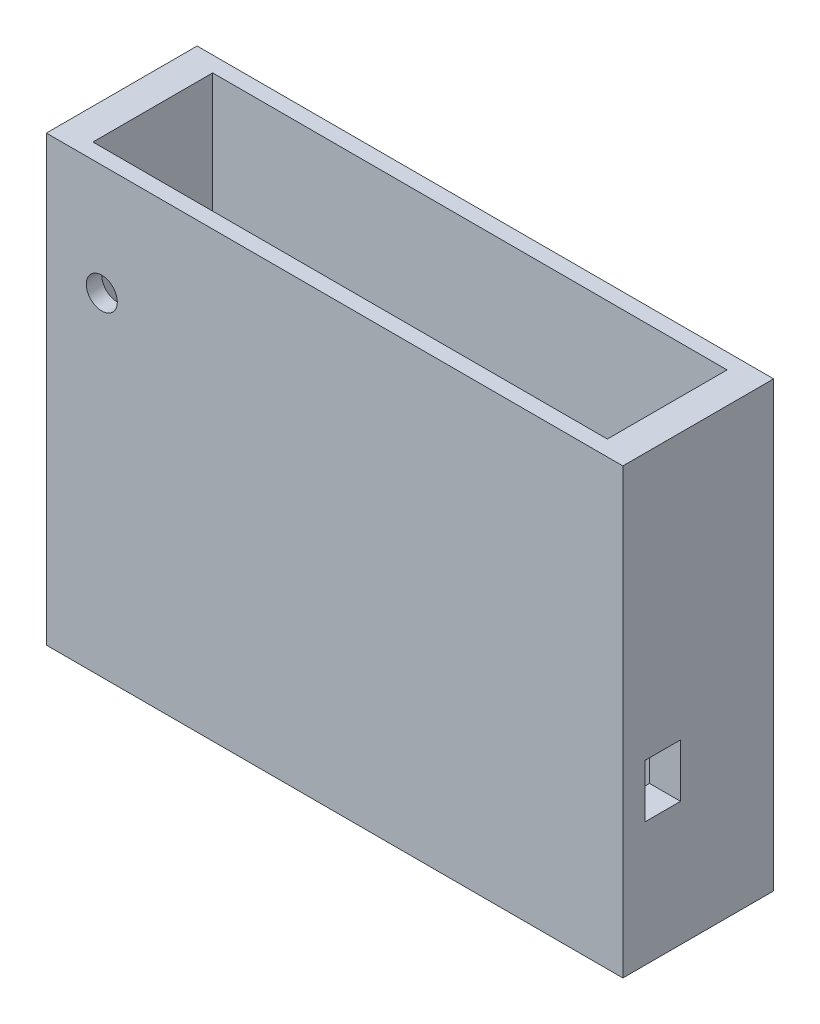
SolidWorks part; units mm, degrees
ref_plane "Plan de face" through (0, 0, 0) normal (0, 0, 1) x (1, 0, 0)
ref_plane "Plan de dessus" through (0, 0, 0) normal (0, 1, 0) x (1, 0, 0)
ref_plane "Plan de droite" through (0, 0, 0) normal (1, 0, 0) x (0, 0, -1)
sketch "Esquisse1" plane through (0, 0, 0) normal (0, 0, 1) x (1, 0, 0)
  line L0 (-65.1774, 60.7604) -> (64.8226, 60.7604)
  line L1 (-65.1774, 60.7604) -> (-65.1774, -39.2396)
  line L2 (64.8226, 60.7604) -> (64.8226, -39.2396)
  line L3 (-65.1774, -39.2396) -> (64.8226, -39.2396)
  circle A0 centre (-52.6774, 35.7604) radius 5.2701
  dimension "D1" = 130
  dimension "D2" = 100
  dimension "D3" = 25
  dimension "D4" = 12.5
extrude "Boss.-Extru.1" add sketch "Esquisse1" along normal blind 34 contours L0 L2 L3 L1
sketch "Esquisse2" plane through (0, -39.2396, 0) normal (0, -1, 0) x (1, 0, 0)
  line L0 (-58.1774, 30.5) -> (57.8226, 30.5)
  line L1 (-58.1774, 30.5) -> (-58.1774, 3.5)
  line L2 (57.8226, 30.5) -> (57.8226, 3.5)
  line L3 (-58.1774, 3.5) -> (57.8226, 3.5)
  line L4 (-65.1774, 0) -> (64.8226, 0) construction
  line L5 (-65.1774, 34) -> (-65.1774, 0) construction
  line L7 (64.8226, 34) -> (64.8226, 0) construction
  line L8 (-65.1774, 34) -> (64.8226, 34) construction
  dimension "D1" = 3.5
  dimension "D2" = 7
  dimension "D3" = 7
  dimension "D4" = 7
  dimension "D5" = 3.5
extrude "Enlèv. mat.-Extru.1" cut sketch "Esquisse2" against normal blind 106 contours L0 L1 L3 L2
sketch "Esquisse3" plane through (0, 0, 34) normal (0, 0, 1) x (1, 0, 0)
  line L0 (-65.1774, 60.7604) -> (64.8226, 60.7604) construction
  line L1 (-65.1774, 60.7604) -> (-65.1774, -39.2396) construction
  circle A0 centre (-52.6774, 35.7604) radius 3.5
  dimension "D3" = 7
  dimension "D1" = 25
  dimension "D2" = 12.5
extrude "Enlèv. mat.-Extru.2" cut sketch "Esquisse3" against normal blind 10 contours A0
sketch "Esquisse4" plane through (64.8226, 0, 0) normal (1, 0, 0) x (0, 0, -1)
  line L0 (-29, 0.7604) -> (-29, -11.2396)
  line L1 (-29, 0.7604) -> (-21, 0.7604)
  line L2 (-29, -11.2396) -> (-21, -11.2396)
  line L3 (-21, 0.7604) -> (-21, -11.2396)
  line L5 (-34, 60.7604) -> (0, 60.7604) construction
  line L6 (0, 60.7604) -> (0, -39.2396) construction
  line L7 (-34, 60.7604) -> (-34, -39.2396) construction
  dimension "D1" = 12
  dimension "D2" = 8
  dimension "D3" = 60
  dimension "D4" = 21
extrude "Enlèv. mat.-Extru.3" cut sketch "Esquisse4" against normal blind 10
